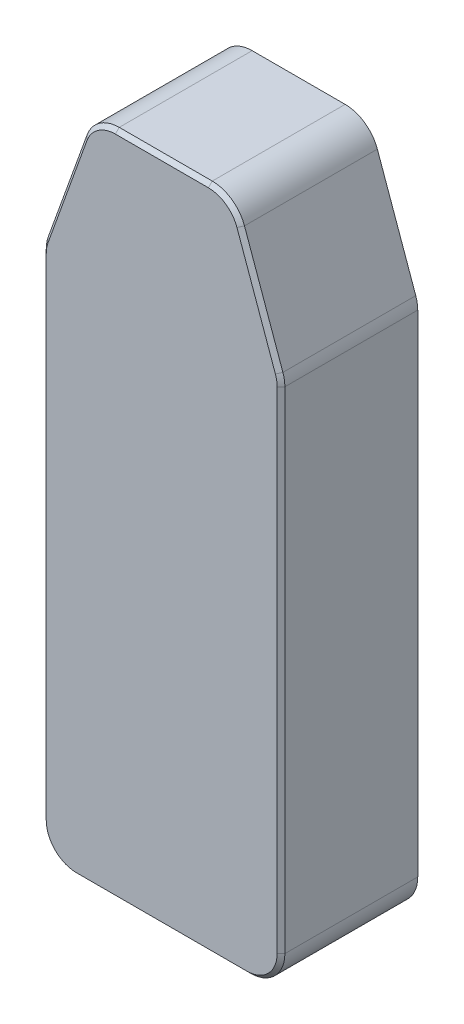
SolidWorks part; units mm, degrees
ref_plane "Front Plane" through (0, 0, 0) normal (0, 0, 1) x (1, 0, 0)
ref_plane "Top Plane" through (0, 0, 0) normal (0, 1, 0) x (1, 0, 0)
ref_plane "Right Plane" through (0, 0, 0) normal (1, 0, 0) x (0, 0, -1)
sketch "Sketch1" plane through (0, 0, 0) normal (0, 0, 1) x (1, 0, 0)
  line L6 (-42.6423, 80.729) -> (-27.5892, 122.4768)
  line L7 (-43.25, -113) -> (-43.25, 77.2522)
  line L8 (-42.6423, 80.729) -> (-27.5892, 122.4768)
  line L9 (-43.25, -113) -> (-43.25, 77.2522)
  line L11 (-43.25, -113) -> (-43.25, 77.2522)
  line L12 (-43.25, -113) -> (-43.25, 77.2522)
  line L36 (43.25, -113) -> (43.25, 77.2693)
  line L37 (42.6538, 80.7141) -> (27.763, 122.4448)
  line L38 (18.1092, 129.25) -> (-17.9469, 129.25)
  line L39 (-27.5892, 122.4768) -> (-42.6423, 80.729)
  line L40 (-43.25, 77.2522) -> (-43.25, -113)
  line L41 (-33, -123.25) -> (33, -123.25)
  line L43 (46.25, -113) -> (46.25, 77.2693)
  line L44 (45.4793, 81.7223) -> (30.5885, 123.453)
  line L45 (18.1092, 132.25) -> (-17.9469, 132.25)
  line L46 (-30.4113, 123.4944) -> (-45.4645, 81.7466)
  line L47 (-46.25, 77.2522) -> (-46.25, -113)
  line L48 (-33, -126.25) -> (33, -126.25)
  arc A3 (-42.6423, 80.729) -> (-43.25, 77.2522) centre (-33, 77.2522) ccw
  arc A4 (-42.6423, 80.729) -> (-43.25, 77.2522) centre (-33, 77.2522) ccw
  arc A6 (-42.6423, 80.729) -> (-43.25, 77.2522) centre (-33, 77.2522) ccw
  arc A7 (-42.6423, 80.729) -> (-43.25, 77.2522) centre (-33, 77.2522) ccw
  arc A31 (33, -123.25) -> (43.25, -113) centre (33, -113) ccw
  arc A32 (43.25, 77.2693) -> (42.6538, 80.7141) centre (33, 77.2693) ccw
  arc A33 (27.763, 122.4448) -> (18.1092, 129.25) centre (18.1092, 119) ccw
  arc A34 (-17.9469, 129.25) -> (-27.5892, 122.4768) centre (-17.9469, 119) ccw
  arc A35 (-42.6423, 80.729) -> (-43.25, 77.2522) centre (-33, 77.2522) ccw
  arc A36 (-43.25, -113) -> (-33, -123.25) centre (-33, -113) ccw
  arc A37 (33, -126.25) -> (46.25, -113) centre (33, -113) ccw
  arc A38 (46.25, 77.2693) -> (45.4793, 81.7223) centre (33, 77.2693) ccw
  arc A39 (30.5885, 123.453) -> (18.1092, 132.25) centre (18.1092, 119) ccw
  arc A40 (-17.9469, 132.25) -> (-30.4113, 123.4944) centre (-17.9469, 119) ccw
  arc A41 (-45.4645, 81.7466) -> (-46.25, 77.2522) centre (-33, 77.2522) ccw
  arc A42 (-46.25, -113) -> (-33, -126.25) centre (-33, -113) ccw
  dimension "D1" = 0.25
  dimension "D2" = 0.25
  dimension "D3" = 3
extrude "Boss-Extrude1" add sketch "Sketch1" along normal blind 50 contours L47 A42 L48 A37 L43 A38 L44 A39 L45 A40 L46 A41 A36 L9 A4 L8 A34 L38 A33 L37 A32 L36 A31 L41
sketch "Sketch3" plane through (0, 0, 50) normal (0, 0, 1) x (1, 0, 0)
  line L6 (-46.25, 77.2522) -> (-46.25, -113)
  line L7 (-33, -126.25) -> (33, -126.25)
  line L8 (46.25, -113) -> (46.25, 77.2693)
  line L9 (45.4793, 81.7223) -> (30.5885, 123.453)
  line L10 (18.1092, 132.25) -> (-17.9469, 132.25)
  line L11 (-30.4113, 123.4944) -> (-45.4645, 81.7466)
  line L12 (-46.25, 77.2522) -> (-46.25, -113)
  line L13 (-33, -126.25) -> (33, -126.25)
  line L14 (46.25, -113) -> (46.25, 77.2693)
  line L15 (45.4793, 81.7223) -> (30.5885, 123.453)
  line L16 (18.1092, 132.25) -> (-17.9469, 132.25)
  line L17 (-30.4113, 123.4944) -> (-45.4645, 81.7466)
  arc A6 (-46.25, -113) -> (-33, -126.25) centre (-33, -113) ccw
  arc A7 (33, -126.25) -> (46.25, -113) centre (33, -113) ccw
  arc A8 (46.25, 77.2693) -> (45.4793, 81.7223) centre (33, 77.2693) ccw
  arc A9 (30.5885, 123.453) -> (18.1092, 132.25) centre (18.1092, 119) ccw
  arc A10 (-17.9469, 132.25) -> (-30.4113, 123.4944) centre (-17.9469, 119) ccw
  arc A11 (-45.4645, 81.7466) -> (-46.25, 77.2522) centre (-33, 77.2522) ccw
  arc A12 (-46.25, -113) -> (-33, -126.25) centre (-33, -113) ccw
  arc A13 (33, -126.25) -> (46.25, -113) centre (33, -113) ccw
  arc A14 (46.25, 77.2693) -> (45.4793, 81.7223) centre (33, 77.2693) ccw
  arc A15 (30.5885, 123.453) -> (18.1092, 132.25) centre (18.1092, 119) ccw
  arc A16 (-17.9469, 132.25) -> (-30.4113, 123.4944) centre (-17.9469, 119) ccw
  arc A17 (-45.4645, 81.7466) -> (-46.25, 77.2522) centre (-33, 77.2522) ccw
  dimension "D1" = 0
extrude "Boss-Extrude2" add sketch "Sketch3" along normal blind 3
chamfer "Chamfer1" distance 1.5 angle 45 24 edges at (-37.9379, 102.6205, 53) (-25.563, 129.8423, 53) (0.0812, 132.25, 53) (25.7433, 129.8297, 53) (38.0339, 102.5876, 53) (46.0559, 79.5289, 53) (46.25, -17.8654, 53) (42.3692, -122.3692, 53) (0, -126.25, 53) (-42.3692, -122.3692, 53) (-46.25, -17.8739, 53) (-46.0521, 79.5335, 53) (35.2084, 101.5794, 0) (43.0999, 79.0173, 0) (24.0148, 127.3777, 0) (43.25, -17.8654, 0) (0.0812, 129.25, 0) (40.2478, -120.2478, 0) (-23.8386, 127.3875, 0) (0, -123.25, 0) (-35.1158, 101.6029, 0) (-40.2478, -120.2478, 0) (-43.0969, 79.0169, 0) (-43.25, -17.8739, 0)
